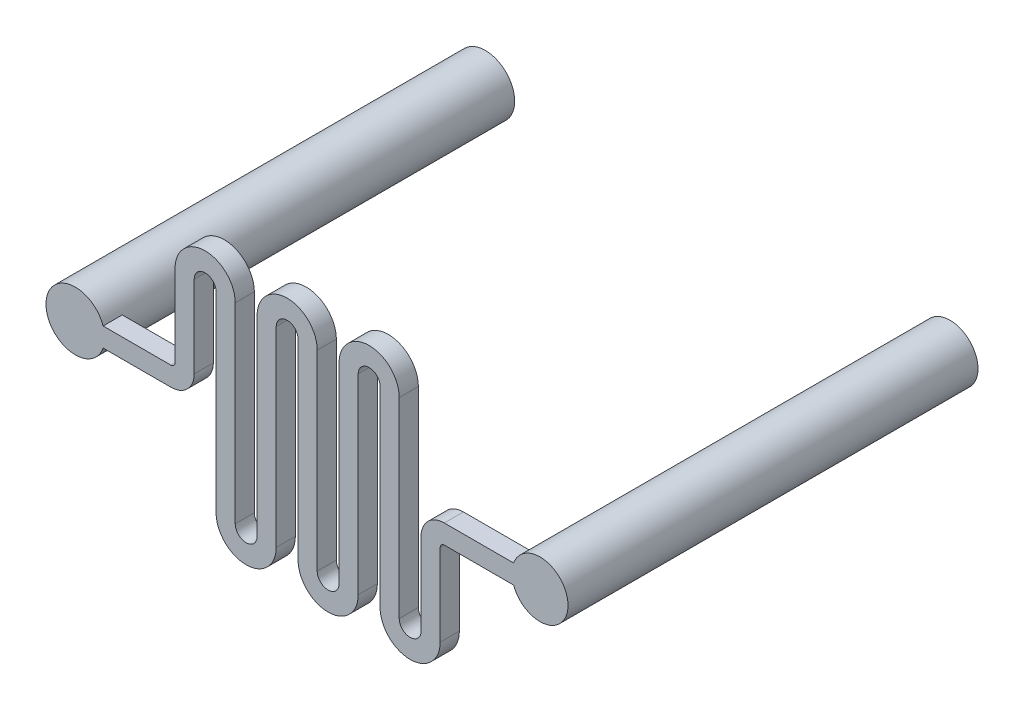
SolidWorks part; units mm, degrees
ref_plane "Front Plane" through (0, 0, 0) normal (0, 0, 1) x (1, 0, 0)
ref_plane "Top Plane" through (0, 0, 0) normal (0, 1, 0) x (1, 0, 0)
ref_plane "Right Plane" through (0, 0, 0) normal (1, 0, 0) x (0, 0, -1)
sketch "Sketch2" plane through (0, 0, 0) normal (0, 0, 1) x (1, 0, 0)
  line L3 (-20.5, -0.7) -> (-13.5, -0.7)
  line L6 (-11.8, 1) -> (-11.8, 7)
  line L9 (-10.2, 7) -> (-10.2, 0)
  line L12 (-10.2, 0) -> (-10.2, -7)
  line L15 (-5.8, -7) -> (-5.8, 0)
  line L18 (-5.8, 0) -> (-5.8, 7)
  line L21 (-4.2, 7) -> (-4.2, 0)
  line L22 (-4.2, 0) -> (-4.2, -7)
  line L23 (0.2, -7) -> (0.2, 0)
  line L24 (0.2, 0) -> (0.2, 7)
  line L25 (1.8, 7) -> (1.8, 0)
  line L26 (1.8, 0) -> (1.8, -7)
  line L27 (6.2, -7) -> (6.2, -1)
  line L28 (6.5, -0.7) -> (13.5, -0.7)
  line L29 (-20.5, 0.7) -> (-13.5, 0.7)
  line L30 (-13.2, 1) -> (-13.2, 7)
  line L31 (-8.8, 7) -> (-8.8, 0)
  line L32 (-8.8, 0) -> (-8.8, -7)
  line L33 (-7.2, -7) -> (-7.2, 0)
  line L34 (-7.2, 0) -> (-7.2, 7)
  line L35 (-2.8, 7) -> (-2.8, 0)
  line L36 (-2.8, 0) -> (-2.8, -7)
  line L37 (-1.2, -7) -> (-1.2, 0)
  line L38 (-1.2, 0) -> (-1.2, 7)
  line L39 (3.2, 7) -> (3.2, 0)
  line L40 (3.2, 0) -> (3.2, -7)
  line L41 (4.8, -7) -> (4.8, -1)
  line L42 (6.5, 0.7) -> (13.5, 0.7)
  arc A8 (-11.8, 1) -> (-13.5, -0.7) centre (-13.5, 1) cw
  arc A9 (-11.8, 7) -> (-10.2, 7) centre (-11, 7) cw
  arc A10 (-10.2, -7) -> (-5.8, -7) centre (-8, -7) ccw
  arc A11 (-5.8, 7) -> (-4.2, 7) centre (-5, 7) cw
  arc A12 (-4.2, -7) -> (0.2, -7) centre (-2, -7) ccw
  arc A13 (0.2, 7) -> (1.8, 7) centre (1, 7) cw
  arc A14 (1.8, -7) -> (6.2, -7) centre (4, -7) ccw
  arc A15 (6.2, -1) -> (6.5, -0.7) centre (6.5, -1) cw
  arc A16 (-13.2, 1) -> (-13.5, 0.7) centre (-13.5, 1) cw
  arc A17 (-13.2, 7) -> (-8.8, 7) centre (-11, 7) cw
  arc A18 (-8.8, -7) -> (-7.2, -7) centre (-8, -7) ccw
  arc A19 (-7.2, 7) -> (-2.8, 7) centre (-5, 7) cw
  arc A20 (-2.8, -7) -> (-1.2, -7) centre (-2, -7) ccw
  arc A21 (-1.2, 7) -> (3.2, 7) centre (1, 7) cw
  arc A22 (3.2, -7) -> (4.8, -7) centre (4, -7) ccw
  arc A23 (4.8, -1) -> (6.5, 0.7) centre (6.5, -1) cw
  arc A24 (-20.5, 0.7) -> (-20.5, -0.7) centre (-20.5, 0) ccw
  arc A25 (13.5, -0.7) -> (13.5, 0.7) centre (13.5, 0) ccw
  point P4 (0, 0)
  point P32 (5.5, 0)
  point P35 (-12.5, 0)
  dimension "D14" = 8
extrude "Boss-Extrude1" add sketch "Sketch2" along normal blind 1.4
ref_plane "Plane1" through (0, 0, 0) normal (0, 1, 0) x (1, 0, 0)
sketch "Sketch3" plane through (0, 0, 0) normal (0, 1, 0) x (1, 0, 0)
  line L1 (-20.5, 28.6) -> (-22.65, 28.6)
  line L2 (-20.5, -1.4) -> (-20.5, 28.6)
  line L6 (-22.65, 28.6) -> (-22.65, -1.4)
  line L7 (-22.65, -1.4) -> (-20.5, -1.4)
  dimension "D1" = 2.15
  dimension "D3" = 30
ref_plane "Plane2" through (0, 0, 0) normal (0, 1, 0) x (1, 0, 0)
sketch "Sketch4" plane through (0, 0, 0) normal (0, 1, 0) x (1, 0, 0)
  line L1 (13.5, 28.6) -> (15.5523, 28.6)
  line L2 (13.5, -1.4) -> (13.5, 28.6)
  line L6 (15.5523, 28.6) -> (15.5523, -1.4)
  line L7 (15.5523, -1.4) -> (13.5, -1.4)
  dimension "D3" = 30
revolve "Revolve1" add sketch "Sketch3" angle 360 about L2
revolve "Revolve2" add sketch "Sketch4" angle 360 about L2
sketch "Sketch5" plane through (0, 0, -28.6) normal (0, 0, -1) x (-1, 0, 0)
  circle A0 centre (-13.5, 0) radius 1.5
  circle A1 centre (20.5, 0) radius 1.5
  dimension "D1" = 3
  dimension "D2" = 3
extrude "Cut-Extrude1" cut sketch "Sketch5" against normal blind 28
